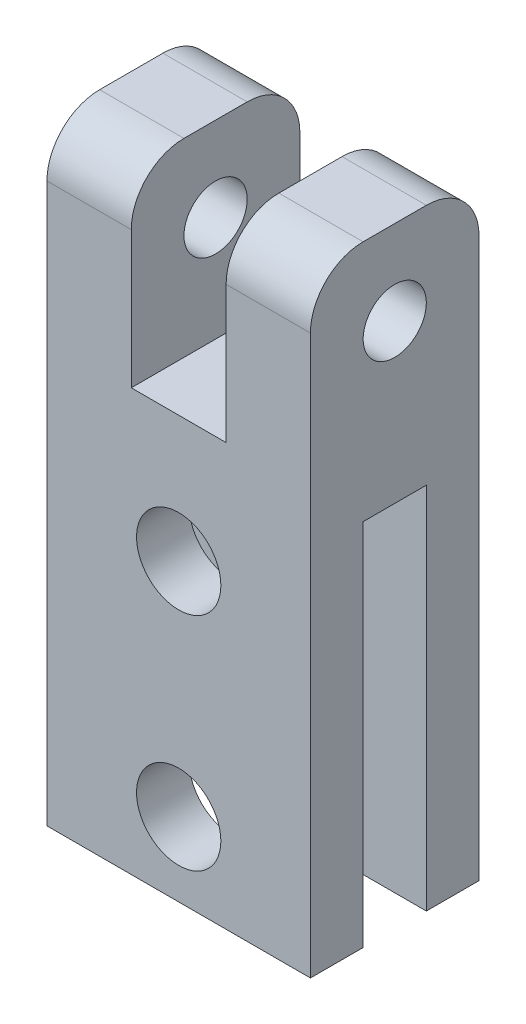
SolidWorks part; units mm, degrees
material "Alüminyum"
ref_plane "Ön Düzlem" through (0, 0, 0) normal (0, 0, 1) x (1, 0, 0)
ref_plane "Üst Düzlem" through (0, 0, 0) normal (0, 1, 0) x (1, 0, 0)
ref_plane "Sağ Düzlem" through (0, 0, 0) normal (1, 0, 0) x (0, 0, -1)
sketch "Çizim1" plane through (0, 0, 0) normal (0, 0, 1) x (1, 0, 0)
  line L0 (-12.5, 28) -> (-12.5, -7)
  line L1 (-12.5, -7) -> (12.5, -7)
  line L2 (12.5, -7) -> (12.5, 28)
  line L3 (-12.5, 28) -> (-12.5, 53)
  line L4 (-12.5, 53) -> (-6, 53)
  line L5 (12.5, 53) -> (12.5, 28)
  line L6 (-6, 53) -> (-6, 33) construction
  line L7 (-6, 33) -> (6, 33) construction
  line L8 (6, 33) -> (6, 53) construction
  line L9 (6, 53) -> (12.5, 53)
  line L10 (0, 33) -> (0, 53) construction
  line L11 (4.5, 33) -> (4.5, 53)
  line L12 (-4.5, 33) -> (-4.5, 53)
  line L13 (-6, 53) -> (-4.5, 53)
  line L14 (-4.5, 33) -> (4.5, 33)
  line L15 (4.5, 53) -> (6, 53)
  circle A0 centre (0, 21) radius 4
  circle A1 centre (0, 0) radius 4
  dimension "D1" = 4.5
  dimension "D2" = 4.5
extrude "Yükseklik-Ekstrüzyon1" add sketch "Çizim1" along normal blind 16
sketch "Çizim2" plane through (0, -7, 0) normal (0, -1, 0) x (1, 0, 0)
  line L0 (-12.5, 8) -> (12.5, 8) construction
  line L1 (-12.5, 16) -> (-12.5, 0) construction
  line L2 (12.5, 16) -> (12.5, 0) construction
  line L3 (-12.5, 5) -> (12.5, 5)
  line L4 (-12.5, 11) -> (12.5, 11)
  line L5 (-12.5, 11) -> (-12.5, 5)
  line L6 (12.5, 11) -> (12.5, 5)
  dimension "D1" = 3
  dimension "D2" = 3
extrude "Kes-Ekstrüzyon1" cut sketch "Çizim2" against normal blind 35
sketch "Çizim3" plane through (4.5, 0, 0) normal (-1, 0, 0) x (0, 0, 1)
  line L0 (16, 53) -> (0, 33) construction
  circle A0 centre (8, 43) radius 3
  dimension "D1" = 6
extrude "Kes-Ekstrüzyon2" cut sketch "Çizim3" against normal blind 20 and the other way blind 36
sketch "Sketch2" plane through (0, 53, 0) normal (0, 1, 0) x (1, 0, 0)
  line L1 (23.1767, -23.7278) -> (-23.2104, -23.7278)
  line L2 (23.1767, -23.7278) -> (23.1767, 5.034)
  line L3 (23.1767, 5.034) -> (-23.2104, 5.034)
  line L4 (-23.2104, -23.7278) -> (-23.2104, 5.034)
extrude "Cut-Extrude1" cut sketch "Sketch2" against normal blind 2
fillet "Fillet1" radius 5 4 edges at (-8.5, 51, 0) (8.5, 51, 0) (-8.5, 51, 16) (8.5, 51, 16)
